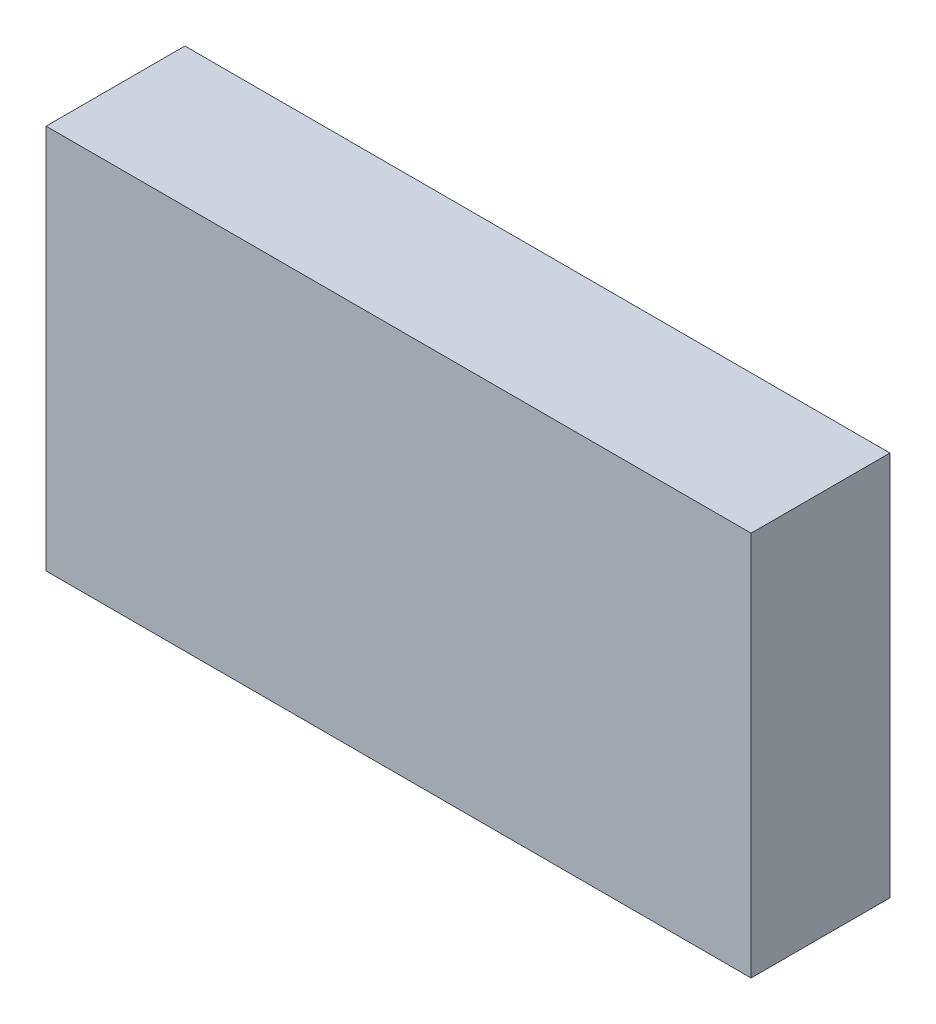
SolidWorks part; units mm, degrees
ref_plane "Front Plane" through (0, 0, 0) normal (0, 0, 1) x (1, 0, 0)
ref_plane "Top Plane" through (0, 0, 0) normal (0, 1, 0) x (1, 0, 0)
ref_plane "Right Plane" through (0, 0, 0) normal (1, 0, 0) x (0, 0, -1)
sketch "Sketch1" plane through (0, 0, 0) normal (0, 0, 1) x (1, 0, 0)
  line L0 (-1.37, -1.37) -> (11.53, -1.37)
  line L1 (11.53, -1.37) -> (11.53, 5.6788)
  line L2 (11.53, 5.6788) -> (-1.37, 5.6788)
  line L3 (-1.37, 5.6788) -> (-1.37, -1.37)
extrude "Component_Outline" add sketch "Sketch1" along normal blind 2.54 separate body
sketch3d "3DSketch1"
  line L0 (0, 0, 0) -> (1, 0, 0)
  line L1 (0, 0, 0) -> (0, 1, 0)
  line L2 (0, 0, 0) -> (0, 0, 1)
  point P0 (0, 0, 0)
